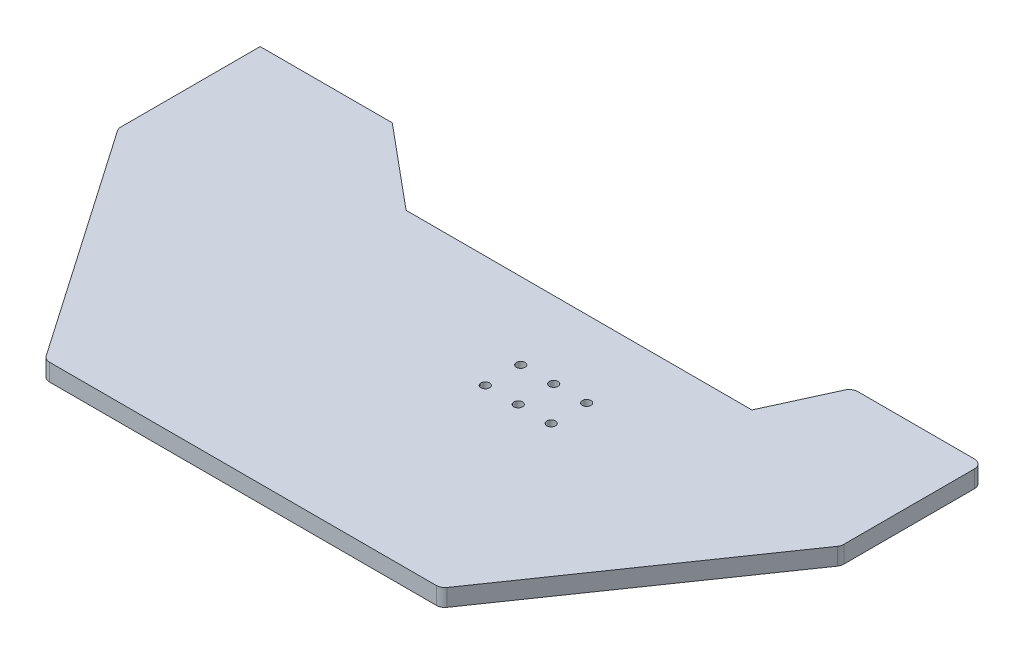
SolidWorks part; units mm, degrees
material "Oak"
ref_plane "Front Plane" through (0, 0, 0) normal (0, 0, 1) x (1, 0, 0)
ref_plane "Top Plane" through (0, 0, 0) normal (0, 1, 0) x (1, 0, 0)
ref_plane "Right Plane" through (0, 0, 0) normal (1, 0, 0) x (0, 0, -1)
sketch "Sketch1" plane through (0, 0, 0) normal (0, 1, 0) x (1, 0, 0)
  line L0 (-266.7, -139.7) -> (266.7, -139.7)
  line L1 (-266.7, -139.7) -> (-266.7, 139.7)
  line L2 (-266.7, 139.7) -> (-169.2275, 139.7)
  line L3 (-169.2275, 139.7) -> (-108.2377, 88.9)
  line L4 (-108.2377, 88.9) -> (146.939, 88.9)
  line L5 (146.939, 88.9) -> (170.18, 139.7)
  line L6 (170.18, 139.7) -> (266.7, 139.7)
  line L7 (266.7, 139.7) -> (266.7, -139.7)
  point P2 (0, -139.7)
  point P4 (266.7, 0)
  dimension "D1" = 96.52
  dimension "D2" = 533.4
  dimension "D3" = 279.4
  dimension "D4" = 50.8
  dimension "D5" = 23.241
  dimension "D6" = 97.4725
  dimension "D7" = 79.375
extrude "Boss-Extrude1" add sketch "Sketch1" along normal mid plane 12.7
sketch "Sketch2" plane through (0, 6.35, 0) normal (0, 1, 0) x (1, 0, 0)
  line L0 (-266.7, -2.0701) -> (266.7, -2.0701) construction
  line L1 (-266.7, 139.7) -> (-266.7, -139.7) construction
  line L2 (266.7, -139.7) -> (266.7, 139.7) construction
  line L3 (266.7, 139.7) -> (170.18, 139.7) construction
  line L4 (32.8422, 32.4104) -> (81.4832, 32.4104) construction
  line L5 (81.4832, 32.4104) -> (81.4832, 6.2484) construction
  line L6 (81.4832, 6.2484) -> (32.8422, 6.2484) construction
  line L7 (32.8422, 6.2484) -> (32.8422, 32.4104) construction
  line L8 (57.1627, 6.2484) -> (57.1627, 32.4104) construction
  circle A0 centre (81.4832, 6.2484) radius 3.175
  circle A1 centre (81.4832, 32.4104) radius 3.175
  circle A2 centre (57.1627, 32.4104) radius 3.175
  circle A3 centre (32.8422, 32.4104) radius 3.175
  circle A4 centre (32.8422, 6.2484) radius 3.175
  circle A5 centre (57.1627, 6.2484) radius 3.175
  dimension "D2" = 6.35
  dimension "D1" = 141.7701
  dimension "D3" = 48.641
  dimension "D4" = 185.2168
  dimension "D5" = 8.3185
  dimension "D6" = 26.162
extrude "Cut-Extrude1" cut sketch "Sketch2" against normal through all
sketch "Sketch3" plane through (0, 6.35, 0) normal (0, 1, 0) x (1, 0, 0)
  line L0 (-266.7, 34.925) -> (-146.05, -139.7)
  line L1 (-266.7, 139.7) -> (-266.7, -139.7) construction
  line L2 (-266.7, -139.7) -> (266.7, -139.7) construction
  line L3 (-146.05, -139.7) -> (-266.7, -139.7)
  line L4 (-266.7, -139.7) -> (-266.7, 34.925)
  dimension "D1" = 174.625
  dimension "D2" = 120.65
extrude "Cut-Extrude2" cut sketch "Sketch3" against normal through all
mirror "Mirror1" about plane through (0, 0, 0) normal (1, 0, 0) of "Cut-Extrude2"
fillet "Fillet1" radius 6.35 6 edges at (170.18, 0, -139.7) (266.7, 0, -139.7) (266.7, 0, -34.925) (146.05, 0, 139.7) (-146.05, 0, 139.7) (-266.7, 0, -34.925)
